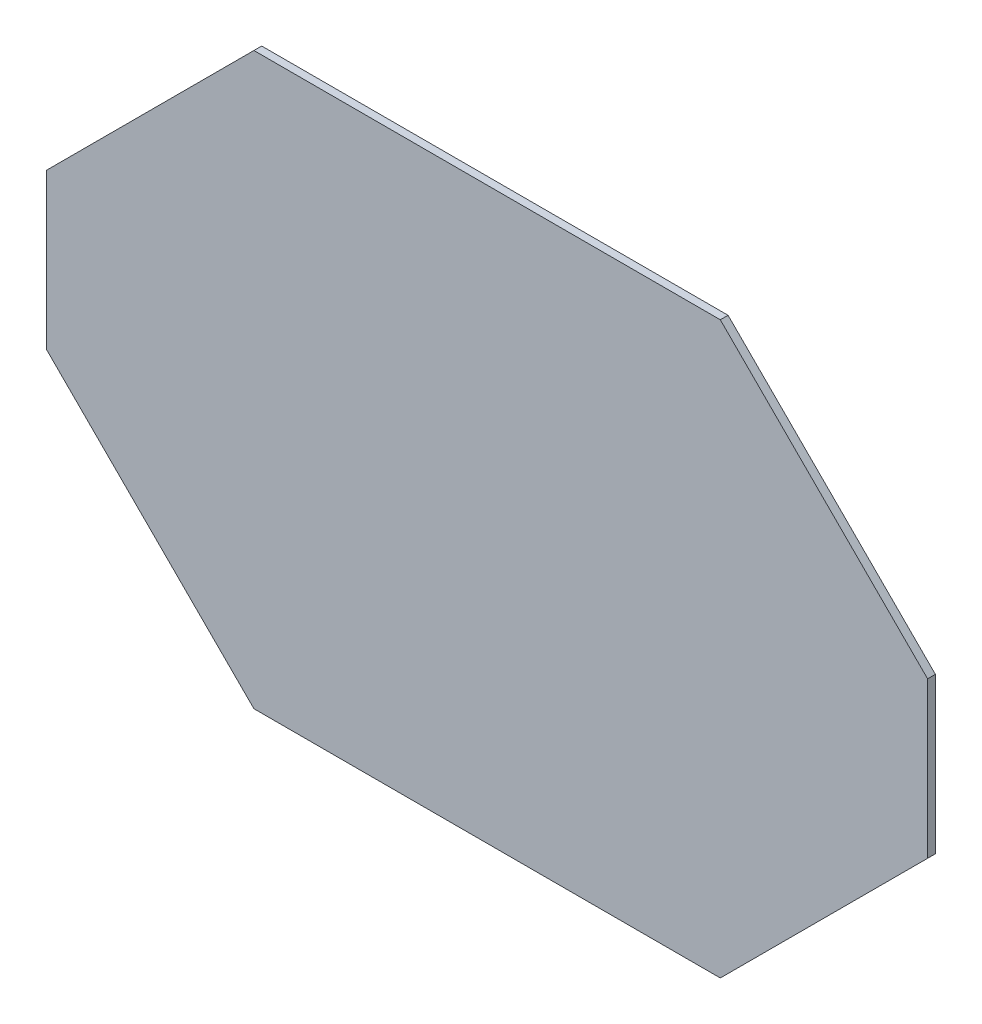
SolidWorks part; units mm, degrees
ref_plane "Front Plane" through (0, 0, 0) normal (0, 0, 1) x (1, 0, 0)
ref_plane "Top Plane" through (0, 0, 0) normal (0, 1, 0) x (1, 0, 0)
ref_plane "Right Plane" through (0, 0, 0) normal (1, 0, 0) x (0, 0, -1)
sketch "Sketch1" plane through (0, 0, 0) normal (0, 0, 1) x (1, 0, 0)
  line L1 (-424.6801, 237.8879) -> (438.9199, 237.8879)
  line L2 (-424.6801, 237.8879) -> (-424.6801, -320.9121)
  line L3 (-424.6801, -320.9121) -> (438.9199, -320.9121)
  line L4 (438.9199, 237.8879) -> (438.9199, -320.9121)
  dimension "D1" = 863.6
  dimension "D2" = 558.8
extrude "Boss-Extrude1" add sketch "Sketch1" along normal blind 7.62
chamfer "Chamfer1" distance 203.2 angle 45 1 edges at (-424.6801, 237.8879, 3.81)
chamfer "Chamfer2" distance 203.2 angle 45 1 edges at (-424.6801, -320.9121, 3.81)
chamfer "Chamfer3" distance 203.2 angle 45 1 edges at (438.9199, -320.9121, 3.81)
chamfer "Chamfer4" distance 203.2 angle 45 1 edges at (438.9199, 237.8879, 3.81)
